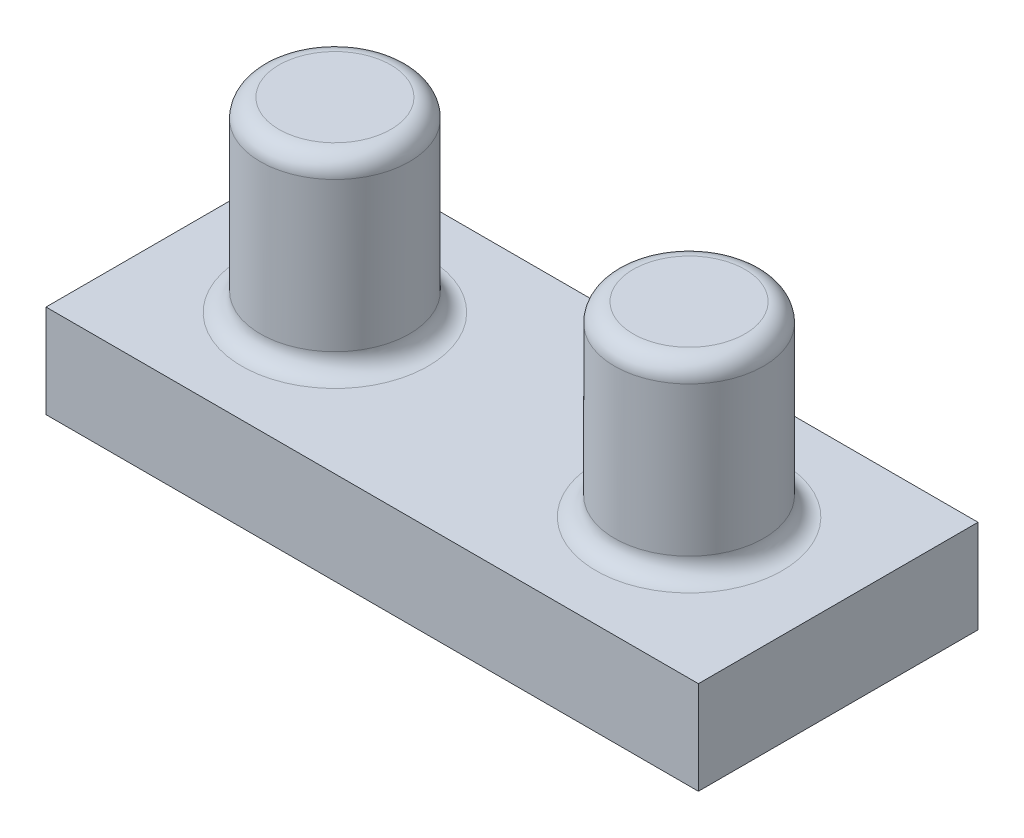
SolidWorks part; units mm, degrees
ref_plane "Front Plane" through (0, 0, 0) normal (0, 0, 1) x (1, 0, 0)
ref_plane "Top Plane" through (0, 0, 0) normal (0, 1, 0) x (1, 0, 0)
ref_plane "Right Plane" through (0, 0, 0) normal (1, 0, 0) x (0, 0, -1)
sketch "Sketch1" plane through (0, 0, 0) normal (0, 1, 0) x (1, 0, 0)
  line L0 (34.9998, 7.1697) -> (-26.696, 7.1697) construction
  circle A0 centre (8.0867, 7.1697) radius 4
  circle A1 centre (-10.9133, 7.1697) radius 4
  point P6 (0, 0)
  dimension "D1" = 19
  dimension "D2" = 8
  dimension "D3" = 8
extrude "Boss-Extrude1" add sketch "Sketch1" along normal blind 10
sketch "Sketch2" plane through (0, 0, 0) normal (0, -1, 0) x (-1, 0, 0)
  line L1 (18.9133, -0.3303) -> (-16.0867, -0.3303)
  line L2 (18.9133, -0.3303) -> (18.9133, 14.6697)
  line L3 (18.9133, 14.6697) -> (-16.0867, 14.6697)
  line L4 (-16.0867, -0.3303) -> (-16.0867, 14.6697)
  circle A0 centre (10.9133, 7.1697) radius 4 construction
  dimension "D1" = 35
  dimension "D2" = 8
  dimension "D3" = 15
  dimension "D4" = 7.5
extrude "Boss-Extrude2" add sketch "Sketch2" along normal blind 5
fillet "Fillet1" radius 1 4 edges at (-10.9133, 0, -11.1697) (8.0867, 0, -3.1697) (-10.9133, 10, -3.1697) (8.0867, 10, -3.1697)
sketch "Sketch3" plane through (0, 0, -14.6697) normal (0, 0, -1) x (-1, 0, 0)
  line L0 (15.3805, -4.4112) -> (-14.2204, -4.4112) construction
  text T0 "19 mm"
extrude "Cut-Extrude1" cut sketch "Sketch3" against normal blind 1
